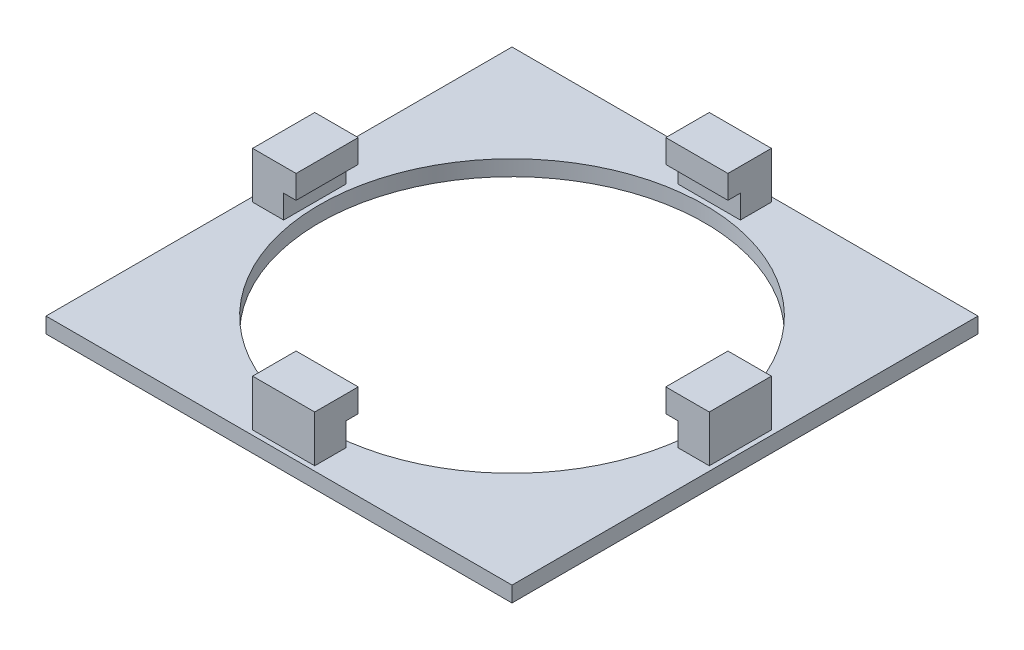
SolidWorks part; units mm, degrees
ref_plane "Front Plane" through (0, 0, 0) normal (0, 0, 1) x (1, 0, 0)
ref_plane "Top Plane" through (0, 0, 0) normal (0, 1, 0) x (1, 0, 0)
ref_plane "Right Plane" through (0, 0, 0) normal (1, 0, 0) x (0, 0, -1)
sketch "Sketch1" plane through (0, 0, 0) normal (0, 1, 0) x (1, 0, 0)
  line L1 (-15, -15) -> (15, -15)
  line L2 (-15, -15) -> (-15, 15)
  line L3 (-15, 15) -> (15, 15)
  line L4 (15, -15) -> (15, 15)
  line L5 (-15, -15) -> (15, 15) construction
  line L6 (-15, 15) -> (15, -15) construction
  point P0 (0, 0)
  dimension "D1" = 30
  dimension "D2" = 30
extrude "Boss-Extrude1" add sketch "Sketch1" along normal blind 1
sketch "Sketch2" plane through (0, 1, 0) normal (0, 1, 0) x (1, 0, 0)
  circle A0 centre (0, 0) radius 12.4
  dimension "D1" = 24.8
extrude "Cut-Extrude1" cut sketch "Sketch2" against normal through all
sketch "Sketch4" plane through (0, 1, 0) normal (0, 1, 0) x (1, 0, 0)
  line L0 (15, 0) -> (12.4, 0)
  line L1 (15, -15) -> (15, 15) construction
  line L2 (0, 15) -> (0, -15)
  line L3 (14.7, 2) -> (12.7, 2)
  line L4 (14.7, 2) -> (14.7, -2)
  line L5 (14.7, -2) -> (12.7, -2)
  line L6 (12.7, 2) -> (12.7, -2)
  line L7 (14.7, 2) -> (12.7, -2) construction
  line L8 (14.7, -2) -> (12.7, 2) construction
  line L9 (15, 15) -> (-15, 15) construction
  line L10 (-15, -15) -> (15, -15) construction
  line L11 (-12.4, 0) -> (0, 0)
  line L12 (-14.7, -2) -> (-12.7, -2)
  line L13 (-12.7, 2) -> (-12.7, -2)
  line L14 (-14.7, 2) -> (-12.7, 2)
  line L15 (-14.7, 2) -> (-14.7, -2)
  line L16 (2, 12.7) -> (-2, 12.7)
  line L17 (2, 14.7) -> (2, 12.7)
  line L18 (2, 14.7) -> (-2, 14.7)
  line L19 (-2, 14.7) -> (-2, 12.7)
  line L20 (12.7, -2) -> (12.7, 2)
  line L21 (14.7, -2) -> (12.7, -2)
  line L22 (14.7, -2) -> (14.7, 2)
  line L23 (14.7, 2) -> (12.7, 2)
  line L24 (-2, -12.7) -> (2, -12.7)
  line L25 (-2, -14.7) -> (-2, -12.7)
  line L26 (-2, -14.7) -> (2, -14.7)
  line L27 (2, -14.7) -> (2, -12.7)
  circle A0 centre (0, 0) radius 12.4 construction
  point P7 (13.7, 0)
  point P41 (0, 0)
  dimension "D1" = 0.3
  dimension "D2" = 4
  dimension "D3" = 4
extrude "Boss-Extrude2" add sketch "Sketch4" along normal blind 2 contours L17 L16 L19 L18 | L4 L5 L6 L3 | L27 L24 L25 L26 | L13 L12 L15 L14
sketch "Sketch5" plane through (12.7, 0, 0) normal (-1, 0, 0) x (0, 0, 1)
  line L0 (2, 3) -> (2, 1) construction
  line L1 (-2, 3) -> (2, 3)
  line L2 (-2, 3) -> (-2, 2.5)
  line L3 (-2, 2.5) -> (2, 2.5)
  line L4 (2, 3) -> (2, 2.5)
  dimension "D1" = 0.5
extrude "Boss-Extrude3" add sketch "Sketch5" along normal blind 0.8
sketch "Sketch6" plane through (0, 0, 12.7) normal (0, 0, -1) x (-1, 0, 0)
  line L0 (2, 3) -> (2, 1) construction
  line L1 (-2, 3) -> (2, 3)
  line L2 (-2, 3) -> (-2, 2.5)
  line L3 (-2, 2.5) -> (2, 2.5)
  line L4 (2, 3) -> (2, 2.5)
  dimension "D1" = 0.5
extrude "Boss-Extrude4" add sketch "Sketch6" along normal blind 0.8
sketch "Sketch7" plane through (-12.7, 0, 0) normal (1, 0, 0) x (0, 0, -1)
  line L0 (2, 3) -> (2, 1) construction
  line L1 (-2, 3) -> (2, 3)
  line L2 (-2, 3) -> (-2, 2.5)
  line L3 (-2, 2.5) -> (2, 2.5)
  line L4 (2, 3) -> (2, 2.5)
  dimension "D1" = 0.5
extrude "Boss-Extrude5" add sketch "Sketch7" along normal blind 0.8
sketch "Sketch8" plane through (0, 0, -12.7) normal (0, 0, 1) x (1, 0, 0)
  line L0 (2, 3) -> (2, 1) construction
  line L1 (-2, 3) -> (2, 3)
  line L2 (-2, 3) -> (-2, 2.5)
  line L3 (-2, 2.5) -> (2, 2.5)
  line L4 (2, 3) -> (2, 2.5)
  dimension "D1" = 0.5
extrude "Boss-Extrude6" add sketch "Sketch8" along normal blind 0.8
sketch "Sketch9" plane through (0, 3, 0) normal (0, 1, 0) x (1, 0, 0)
  line L0 (-11.9, 0) -> (11.9, 0)
  line L1 (-11.9, 2) -> (-11.9, -2) construction
  line L2 (11.9, -2) -> (11.9, 2) construction
  line L3 (0, -11.9) -> (0, 11.9)
  line L4 (-2, -11.9) -> (2, -11.9) construction
  line L5 (2, 11.9) -> (-2, 11.9) construction
  line L6 (14.7, 2) -> (11.9, 2)
  line L7 (-14.7, -2) -> (-11.9, -2)
  line L8 (-14.7, -2) -> (-14.7, 2)
  line L9 (-14.7, 2) -> (-11.9, 2)
  line L10 (-11.9, -2) -> (-11.9, 2)
  line L11 (-2, -14.7) -> (2, -14.7)
  line L12 (-2, -14.7) -> (-2, -11.9)
  line L13 (-2, -11.9) -> (2, -11.9)
  line L14 (2, -14.7) -> (2, -11.9)
  line L15 (11.9, -2) -> (11.9, 2)
  line L16 (14.7, -2) -> (11.9, -2)
  line L17 (14.7, -2) -> (14.7, 2)
  line L18 (-2, 11.9) -> (2, 11.9)
  line L19 (2, 14.7) -> (2, 11.9)
  line L20 (-2, 14.7) -> (2, 14.7)
  line L21 (-2, 14.7) -> (-2, 11.9)
extrude "Boss-Extrude7" add sketch "Sketch9" along normal blind 1 contours L11 L14 L13 L12 | L16 L17 L6 L15 | L20 L21 L18 L19
